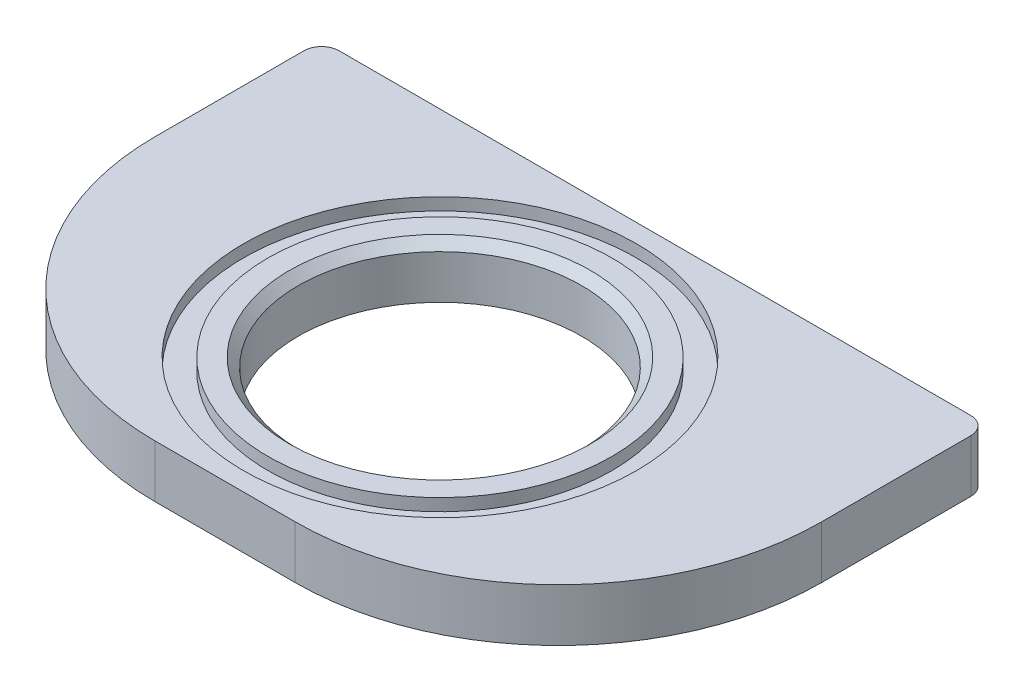
SolidWorks part; units mm, degrees
ref_plane "Front Plane" through (0, 0, 0) normal (0, 0, 1) x (1, 0, 0)
ref_plane "Top Plane" through (0, 0, 0) normal (0, 1, 0) x (1, 0, 0)
ref_plane "Right Plane" through (0, 0, 0) normal (1, 0, 0) x (0, 0, -1)
sketch "Sketch1" plane through (0, 0, 0) normal (0, 1, 0) x (1, 0, 0)
  line L1 (-19, 12.25) -> (19, 12.25)
  line L2 (-19, 12.25) -> (-19, -12.25)
  line L3 (-19, -12.25) -> (19, -12.25)
  line L4 (19, 12.25) -> (19, -12.25)
  circle A0 centre (0, 0) radius 8.075
  dimension "D5" = 16.15
  dimension "D1" = 38
  dimension "D2" = 24.5
  dimension "D3" = 12.25
  dimension "D4" = 19
extrude "Boss-Extrude1" add sketch "Sketch1" along normal blind 3
fillet "Fillet1" radius 15 2 edges at (19, 1.5, 12.25) (-19, 1.5, 12.25)
sketch "Sketch2" plane through (0, 3, 0) normal (0, 1, 0) x (1, 0, 0)
  circle A0 centre (0, 0) radius 10.5
  dimension "D1" = 21
sketch "Sketch3" plane through (0, 0, 0) normal (0, 0, 1) x (1, 0, 0)
  line L0 (10.5, 3) -> (-10.5, 3) construction
  line L1 (9.8, 3.7) -> (11.2, 3.7)
  line L2 (9.8, 3.7) -> (9.8, 2.3)
  line L3 (9.8, 2.3) -> (11.2, 2.3)
  line L4 (11.2, 3.7) -> (11.2, 2.3)
  dimension "D1" = 1.4
  dimension "D2" = 1.4
  dimension "D3" = 9.8
  dimension "D4" = 0.7
sweep "Cut-Sweep1" cut profiles "Sketch3" path "Sketch2"
fillet "Fillet2" radius 1 2 edges at (-19, 1.5, -12.25) (19, 1.5, -12.25)
chamfer "Chamfer1" distance 0.5 angle 45 1 edges at (0, 3, 8.075)
